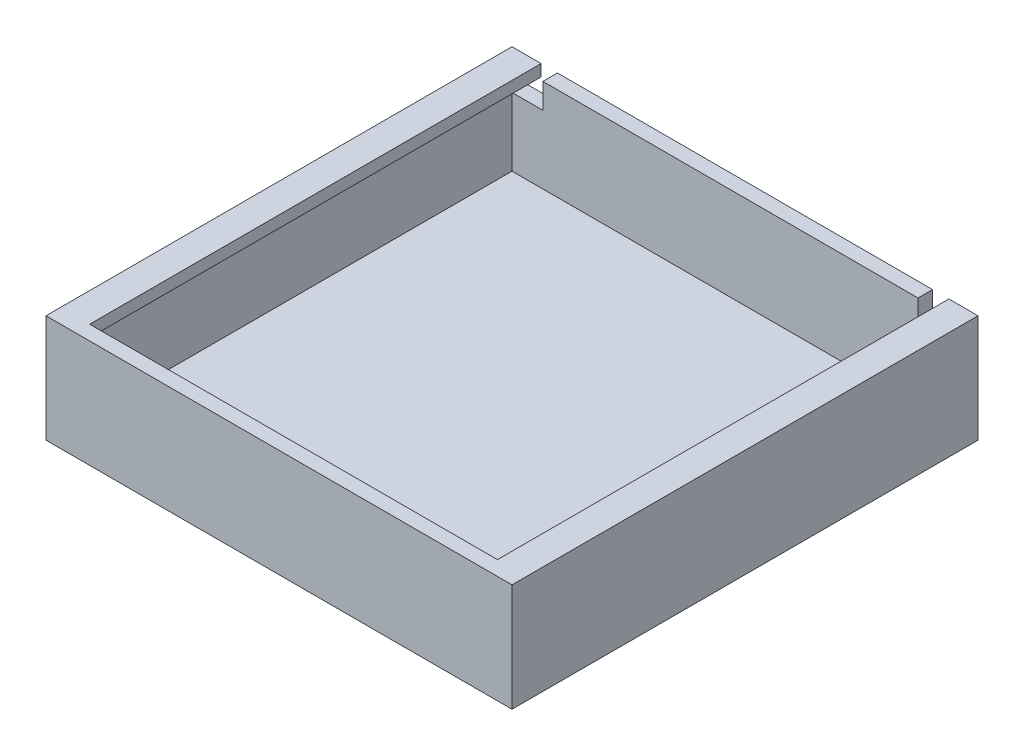
SolidWorks part; units mm, degrees
ref_plane "Front Plane" through (0, 0, 0) normal (0, 0, 1) x (1, 0, 0)
ref_plane "Top Plane" through (0, 0, 0) normal (0, 1, 0) x (1, 0, 0)
ref_plane "Right Plane" through (0, 0, 0) normal (1, 0, 0) x (0, 0, -1)
sketch "Sketch1" plane through (0, 0, 0) normal (0, 1, 0) x (1, 0, 0)
  line L1 (-40, -40) -> (40, -40)
  line L2 (-40, -40) -> (-40, 40)
  line L3 (-40, 40) -> (40, 40)
  line L4 (40, -40) -> (40, 40)
  line L5 (-40, -40) -> (40, 40) construction
  line L6 (-40, 40) -> (40, -40) construction
  point P0 (0, 0)
  dimension "D1" = 80
extrude "Boss-Extrude1" add sketch "Sketch1" along normal blind 2.5 contours L3 L4 L1 L2
sketch "Sketch2" plane through (0, 2.5, 0) normal (0, 1, 0) x (1, 0, 0)
  line L1 (-40, 40) -> (40, 40)
  line L2 (-40, 40) -> (-40, -40)
  line L3 (-40, -40) -> (40, -40)
  line L4 (40, 40) -> (40, -40)
  line L5 (-40, 40) -> (40, -40) construction
  line L6 (-40, -40) -> (40, 40) construction
  line L7 (-37.5, 37.5) -> (37.5, 37.5)
  line L8 (-37.5, 37.5) -> (-37.5, -37.5)
  line L9 (-37.5, -37.5) -> (37.5, -37.5)
  line L10 (37.5, 37.5) -> (37.5, -37.5)
  line L11 (-37.5, 37.5) -> (37.5, -37.5) construction
  line L12 (-37.5, -37.5) -> (37.5, 37.5) construction
  point P0 (0, 0)
  point P7 (0, 0)
  dimension "D1" = 2.5
extrude "Boss-Extrude2" add sketch "Sketch2" along normal blind 16
sketch "Sketch4" plane through (0, 0, 40) normal (0, 0, 1) x (1, 0, 0)
  line L0 (-40, 18.5) -> (-35, 18.5)
  line L1 (-40, 18.5) -> (40, 18.5) construction
  line L2 (-35, 18.5) -> (-35, 16.5)
  line L3 (-35, 16.5) -> (-40, 16.5)
  line L4 (-40, 18.5) -> (-40, 0) construction
  line L5 (-40, 16.5) -> (-40, 18.5)
  line L6 (0, 0) -> (0, 18.5)
  line L7 (-40, 0) -> (40, 0) construction
  line L8 (35, 16.5) -> (40, 16.5)
  line L9 (35, 18.5) -> (35, 16.5)
  line L10 (40, 18.5) -> (35, 18.5)
  line L11 (40, 16.5) -> (40, 18.5)
  line M7 (40, 0) -> (40, 18.5)
  line M8 (40, 18.5) -> (-40, 18.5)
  line M9 (-40, 18.5) -> (-40, 0)
  dimension "D1" = 2
  dimension "D2" = 5
extrude "Boss-Extrude3" add sketch "Sketch4" against normal up to next contours L3 L2 M8 M9 | L9 L8 M8 M7
sketch "Sketch5" plane through (0, 0, -40) normal (0, 0, -1) x (-1, 0, 0)
  line L0 (-40, 18.5) -> (-35, 18.5)
  line L1 (-40, 18.5) -> (40, 18.5) construction
  line L2 (-35, 18.5) -> (-35, 16.5)
  line L3 (-35, 16.5) -> (-37.5, 16.5)
  line L4 (-37.5, 16.5) -> (-37.5, 14.2)
  line L5 (-37.5, 14.2) -> (-32.2, 14.2)
  line L6 (-32.2, 14.2) -> (-32.2, 18.5)
  line L7 (40, 18.5) -> (-40, 18.5) construction
  line L8 (-32.2, 18.5) -> (-35, 18.5)
  line L9 (-40, 18.5) -> (-40, 0) construction
  line L10 (0, 0) -> (0, 18.5)
  line L11 (40, 0) -> (-40, 0) construction
  line L12 (32.2, 18.5) -> (35, 18.5)
  line L13 (32.2, 14.2) -> (32.2, 18.5)
  line L14 (37.5, 14.2) -> (32.2, 14.2)
  line L15 (37.5, 16.5) -> (37.5, 14.2)
  line L16 (35, 16.5) -> (37.5, 16.5)
  line L17 (35, 18.5) -> (35, 16.5)
  line M4 (40, 18.5) -> (-40, 18.5)
  dimension "D1" = 2
  dimension "D2" = 2.5
  dimension "D3" = 2.8
  dimension "D4" = 2.3
  dimension "D5" = 2.5
extrude "Cut-Extrude2" cut sketch "Sketch5" against normal up to surface (2.5 mm away) contours L5 L6 L2 L3 L4 M4 | L17 L13 L14 L15 L16 M4 up to face at (0, 13.5, -37.5)
